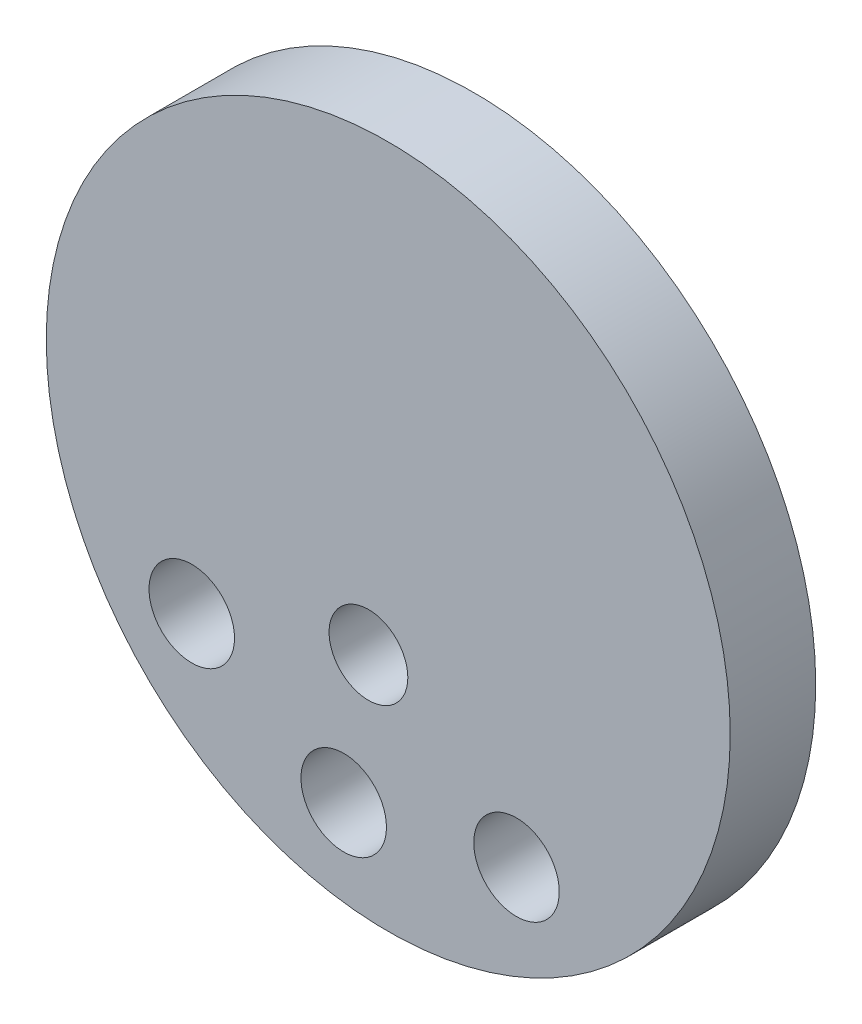
SolidWorks part; units mm, degrees
ref_plane "Front Plane" through (0, 0, 0) normal (0, 0, 1) x (1, 0, 0)
ref_plane "Top Plane" through (0, 0, 0) normal (0, 1, 0) x (1, 0, 0)
ref_plane "Right Plane" through (0, 0, 0) normal (1, 0, 0) x (0, 0, -1)
sketch "Sketch1" plane through (0, 0, 0) normal (0, 0, 1) x (1, 0, 0)
  circle A0 centre (0, 0) radius 20
  dimension "D1" = 40
extrude "Boss-Extrude1" add sketch "Sketch1" along normal blind 5
sketch "Sketch2" plane through (0, 0, 5) normal (0, 0, 1) x (1, 0, 0)
  line L0 (0, 0) -> (-20, 0) construction
  line L1 (0, 0) -> (15.3209, -12.8558) construction
  line L2 (0, 0) -> (3.473, 19.6962) construction
  line L3 (0, 0) -> (-18.7939, -6.8404) construction
  line L4 (0, 0) -> (-11.4907, 9.6418) construction
  circle A0 centre (-15, 0) radius 2.5 construction
  circle A18 centre (0, 0) radius 20 construction
  circle A19 centre (-11.4907, 9.6418) radius 2.5 construction
  circle A20 centre (-2.6047, 14.7721) radius 2.5 construction
  circle A21 centre (7.5, 12.9904) radius 2.5 construction
  circle A22 centre (14.0954, 5.1303) radius 2.5 construction
  circle A23 centre (14.0954, -5.1303) radius 2.5 construction
  circle A24 centre (7.5, -12.9904) radius 2.5
  circle A25 centre (-2.6047, -14.7721) radius 2.5
  circle A26 centre (-11.4907, -9.6418) radius 2.5
  circle A27 centre (-5.107, 4.2853) radius 2.3024 construction
  circle A28 centre (6.2646, 2.2801) radius 2.3024 construction
  circle A29 centre (-1.1577, -6.5654) radius 2.3024
  point P24 (0, 0)
  point P28 (0, 0)
  point P36 (0, 0)
  dimension "D2" = 5
  dimension "D1" = 15
  dimension "D5" = 3
  dimension "D3" = 6.6667
  dimension "D4" = 9
extrude "Cut-Extrude1" cut sketch "Sketch2" against normal blind 35
